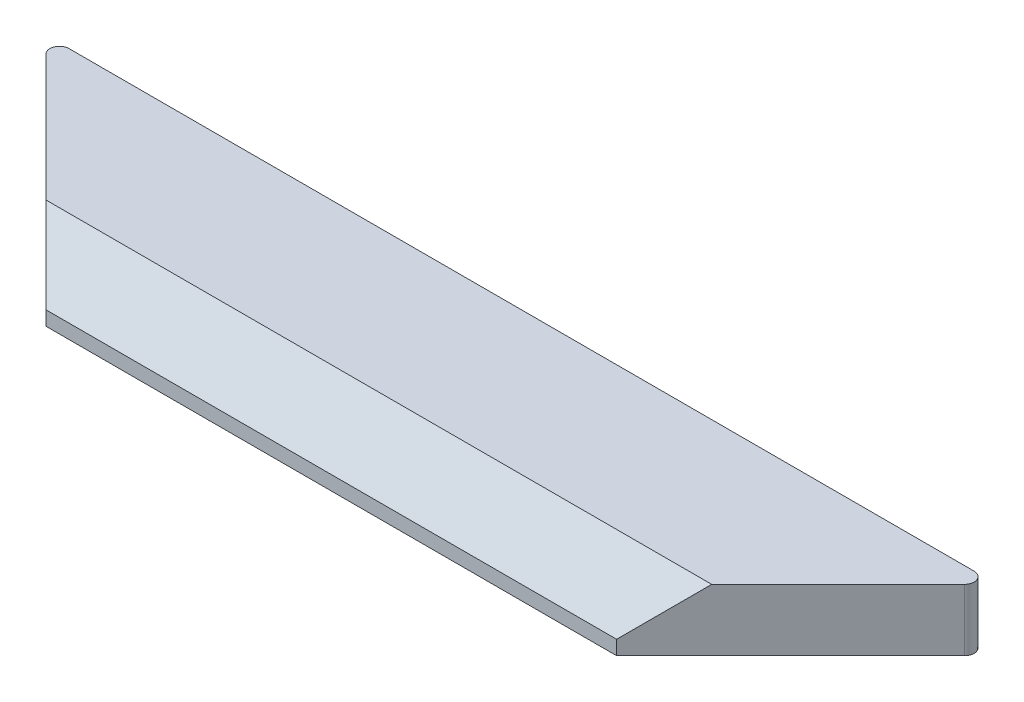
SolidWorks part; units mm, degrees
material "99.5% Aluminum Oxide"
ref_plane "Front Plane" through (0, 0, 0) normal (0, 0, 1) x (1, 0, 0)
ref_plane "Top Plane" through (0, 0, 0) normal (0, 1, 0) x (1, 0, 0)
ref_plane "Right Plane" through (0, 0, 0) normal (1, 0, 0) x (0, 0, -1)
sketch "Sketch1" plane through (0, 0, 0) normal (0, 1, 0) x (1, 0, 0)
  line L0 (-50, 10) -> (-30, -10)
  line L1 (-30, -10) -> (30, -10)
  line L2 (-50, -10) -> (-50, 10) construction
  line L3 (-50, 10) -> (50, 10)
  line L4 (50, -10) -> (50, 10) construction
  line L5 (-50, -10) -> (50, 10) construction
  line L6 (-50, 10) -> (50, -10) construction
  line L7 (50, 10) -> (30, -10)
  line L8 (-50, -10) -> (-30, -10) construction
  line L9 (30, -10) -> (50, -10) construction
  point P0 (0, 0)
  dimension "D1" = 20
  dimension "D2" = 100
  dimension "D3" = 45
extrude "Boss-Extrude1" add sketch "Sketch1" along normal mid plane 6.5
sketch "Sketch2" plane through (0, -3.25, 0) normal (0, -1, 0) x (1, 0, 0)
  line L0 (50, -10) -> (-50, -10) construction
  line L1 (30, 0) -> (-30, 0)
  line L2 (30, 0) -> (30, -10)
  line L3 (30, -10) -> (-30, -10)
  line L4 (-30, 0) -> (-30, -10)
  line L5 (30, 0) -> (-30, -10) construction
  line L6 (30, -10) -> (-30, 0) construction
  point P0 (0, -5)
  point P7 (0, 0)
  point P9 (0, -5.45)
  dimension "D1" = 60
  dimension "D2" = 10
extrude "Cut-Extrude1" cut sketch "Sketch2" against normal blind 4
sketch "Sketch3" plane through (-30, 0, 0) normal (1, 0, 0) x (0, 0, -1)
  line L0 (0, 0.75) -> (10, -3.25) construction
  line L1 (5, -0.25) -> (5, -2.25)
  arc A0 (5, -0.25) -> (5, -2.25) centre (5, -1.25) cw
  dimension "D1" = 1
revolve "Cut-Revolve1" cut sketch "Sketch3" angle 360 about L1
sketch "Sketch4" plane through (30, 0, 0) normal (-1, 0, 0) x (0, 0, 1)
  line L0 (-5, 0.75) -> (-5, -3.25) construction
  line L1 (-10, 0.75) -> (0, 0.75) construction
  line L2 (-10, -3.25) -> (0, -3.25) construction
  line L3 (-5, -0.25) -> (-5, -2.25)
  arc A0 (-5, -0.25) -> (-5, -2.25) centre (-5, -1.25) ccw
  dimension "D1" = 1
revolve "Cut-Revolve2" cut sketch "Sketch4" angle 360 about L0
chamfer "Chamfer1" distance 5 angle 45 1 edges at (0, 3.25, 10)
fillet "Fillet1" radius 1 6 edges at (-30, -1.25, 0) (30, -1.25, 0) (30, -1.25, -10) (-30, -1.25, -10) (-50, 0, -10) (50, 0, -10)
